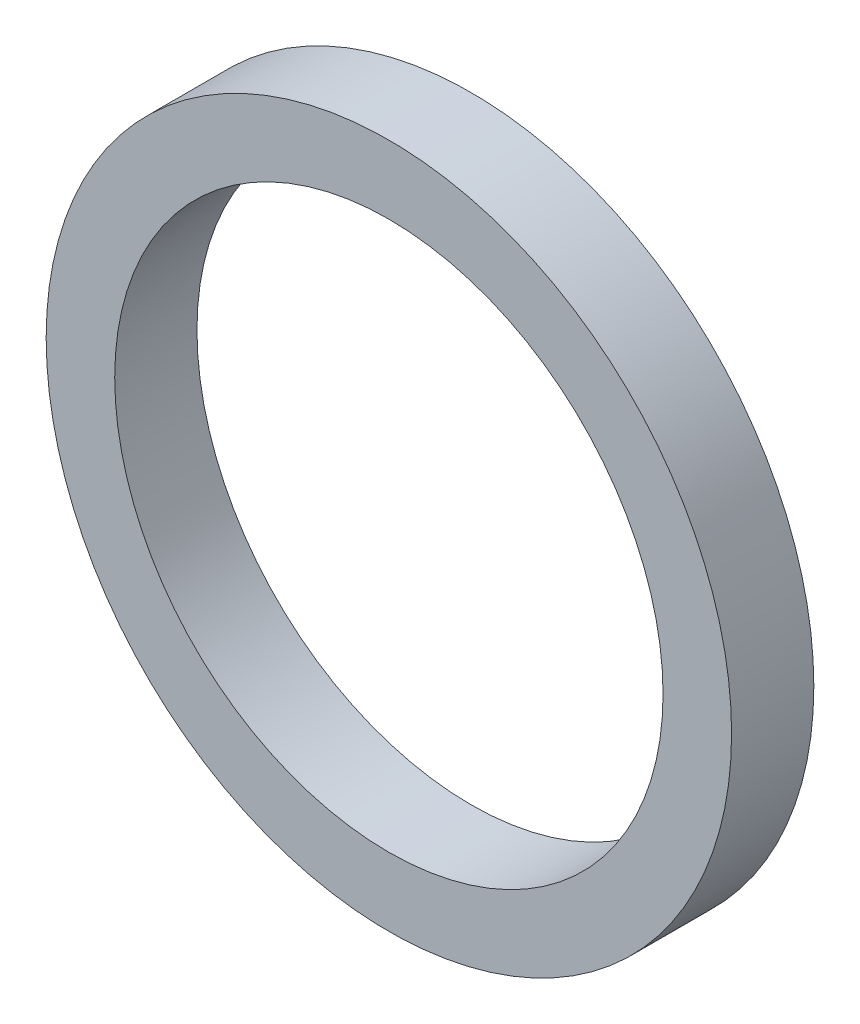
SolidWorks part; units mm, degrees
ref_plane "Front Plane" through (0, 0, 0) normal (0, 0, 1) x (1, 0, 0)
ref_plane "Top Plane" through (0, 0, 0) normal (0, 1, 0) x (1, 0, 0)
ref_plane "Right Plane" through (0, 0, 0) normal (1, 0, 0) x (0, 0, -1)
sketch "Sketch1" plane through (0, 0, 0) normal (0, 0, 1) x (1, 0, 0)
  circle A0 centre (0, 0) radius 20
  circle A1 centre (0, 0) radius 25
  dimension "D1" = 40
  dimension "D2" = 50
extrude "Boss-Extrude1" add sketch "Sketch1" along normal blind 6
